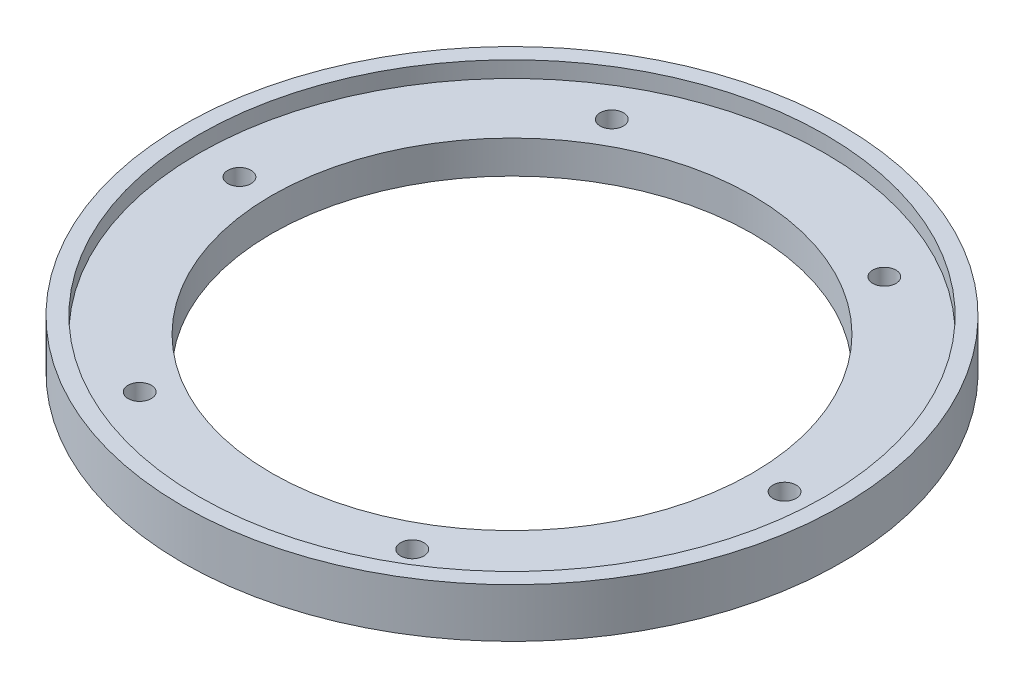
SolidWorks part; units mm, degrees
ref_plane "前视基准面" through (0, 0, 0) normal (0, 0, 1) x (1, 0, 0)
ref_plane "上视基准面" through (0, 0, 0) normal (0, 1, 0) x (1, 0, 0)
ref_plane "右视基准面" through (0, 0, 0) normal (1, 0, 0) x (0, 0, -1)
other "Configuration Table"
sketch "草图1" plane through (0, 0, 0) normal (0, 0, 1) x (1, 0, 0)
  line L0 (0, 0) -> (0, 23.6367) construction
  line L2 (44.5, 0) -> (58, 0)
  line L3 (44.5, 0) -> (44.5, 6.1)
  line L4 (44.5, 6.1) -> (58, 6.1)
  line L6 (58, 9.1) -> (61, 9.1)
  line L7 (58, 9.1) -> (58, 6.1)
  line L9 (61, 9.1) -> (61, 0)
  line L10 (58, 0) -> (61, 0)
  dimension "D1" = 58
  dimension "D2" = 6.1
  dimension "D3" = 44.5
  dimension "D4" = 9.1
  dimension "D5" = 3
revolve "旋转1" add sketch "草图1" angle 360 about L0
sketch "草图3" plane through (0, 6.1, 0) normal (0, 1, 0) x (1, 0, 0)
  circle A0 centre (0, 0) radius 50.45 construction
  circle A2 centre (-50.45, 0) radius 2.15
  circle A3 centre (-25.225, 43.691) radius 2.15
  circle A4 centre (25.225, 43.691) radius 2.15
  circle A5 centre (50.45, 0) radius 2.15
  circle A6 centre (25.225, -43.691) radius 2.15
  circle A7 centre (-25.225, -43.691) radius 2.15
  dimension "D1" = 100.9
  dimension "D2" = 4.3
  dimension "D3" = 6
extrude "切除-拉伸2" cut sketch "草图3" against normal blind 10
